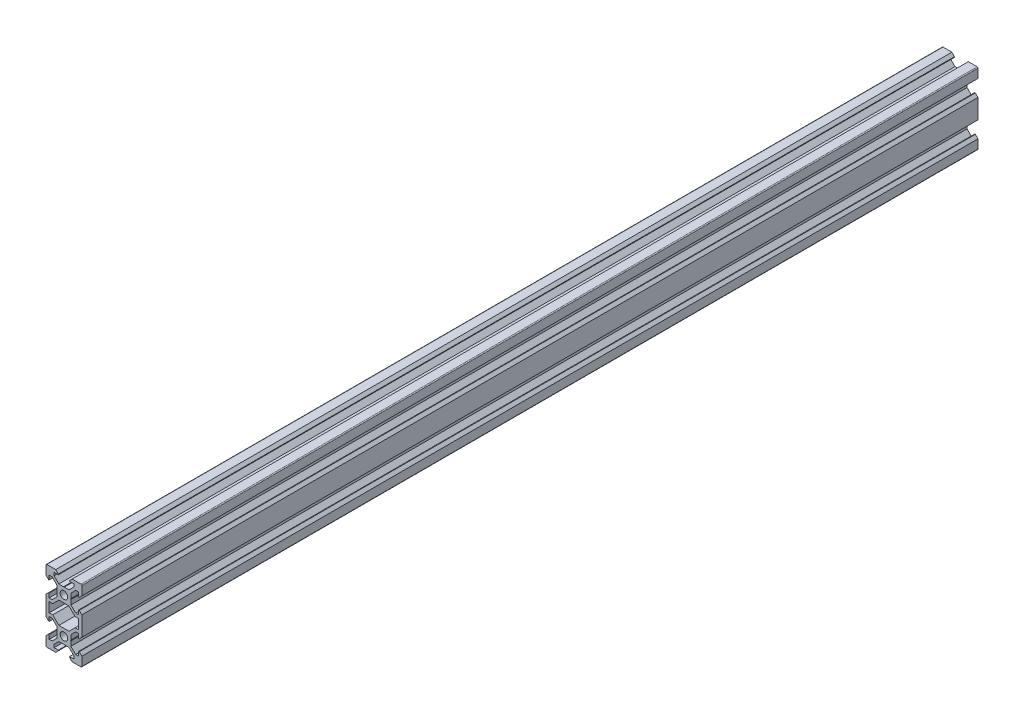
SolidWorks part; units mm, degrees
material "6061-T6 (SS)"
ref_plane "Front Plane" through (0, 0, 0) normal (0, 0, 1) x (1, 0, 0)
ref_plane "Top Plane" through (0, 0, 0) normal (0, 1, 0) x (1, 0, 0)
ref_plane "Right Plane" through (0, 0, 0) normal (1, 0, 0) x (0, 0, -1)
sketch "Sketch1" plane through (0, 0, 0) normal (0, 0, 1) x (1, 0, 0)
  line L0 (0, 0) -> (10, 0) construction
  line L1 (9.5, -20) -> (-9.5, -20)
  line L2 (10, -19.5) -> (10, 19.5)
  line L3 (9.5, 20) -> (-9.5, 20)
  line L4 (-10, -19.5) -> (-10, 19.5)
  line L5 (10, -20) -> (-10, 20) construction
  line L6 (10, 20) -> (-10, -20) construction
  circle A0 centre (0, 10) radius 2.1
  circle A1 centre (0, -10) radius 2.1
  arc A2 (-9.5, -20) -> (-10, -19.5) centre (-9.5, -19.5) cw
  arc A3 (9.5, -20) -> (10, -19.5) centre (9.5, -19.5) ccw
  arc A4 (10, 19.5) -> (9.5, 20) centre (9.5, 19.5) ccw
  arc A5 (-9.5, 20) -> (-10, 19.5) centre (-9.5, 19.5) ccw
  point P0 (0, 0)
  line B0 (0, 10) -> (0, 20) construction
  line B1 (0, 13.69) -> (-0.21, 13.9)
  line B2 (-0.21, 13.9) -> (-2.8393, 13.9)
  line B3 (-2.8393, 13.9) -> (-5.5, 16.5607)
  line B4 (-5.5, 16.5607) -> (-5.5, 18.2)
  line B5 (-5.5, 18.2) -> (-3.125, 18.2)
  line B6 (-3.125, 18.2) -> (-3.125, 18.545)
  line B7 (-3.125, 18.545) -> (-4.58, 20)
  line B8 (-4.58, 20) -> (4.58, 20)
  line B9 (0, 10) -> (-5.9132, 15.9132) construction
  line B10 (3.125, 18.545) -> (4.58, 20)
  line B11 (3.125, 18.2) -> (3.125, 18.545)
  line B12 (5.5, 18.2) -> (3.125, 18.2)
  line B13 (5.5, 16.5607) -> (5.5, 18.2)
  line B14 (2.8393, 13.9) -> (5.5, 16.5607)
  line B15 (0.21, 13.9) -> (2.8393, 13.9)
  line B16 (0, 13.69) -> (0.21, 13.9)
  line B17 (0, 10) -> (-10, 10) construction
  line B18 (-3.69, 10) -> (-3.9, 9.79)
  line B19 (-3.9, 9.79) -> (-3.9, 7.1607)
  line B20 (-3.9, 7.1607) -> (-6.5607, 4.5)
  line B21 (-6.5607, 4.5) -> (-8.2, 4.5)
  line B22 (-8.2, 4.5) -> (-8.2, 6.875)
  line B23 (-8.2, 6.875) -> (-8.545, 6.875)
  line B24 (-8.545, 6.875) -> (-10, 5.42)
  line B25 (-10, 5.42) -> (-10, 14.58)
  line B26 (0, 10) -> (-5.9132, 4.0868) construction
  line B27 (-8.545, 13.125) -> (-10, 14.58)
  line B28 (-8.2, 13.125) -> (-8.545, 13.125)
  line B29 (-8.2, 15.5) -> (-8.2, 13.125)
  line B30 (-6.5607, 15.5) -> (-8.2, 15.5)
  line B31 (-3.9, 12.8393) -> (-6.5607, 15.5)
  line B32 (-3.9, 10.21) -> (-3.9, 12.8393)
  line B33 (-3.69, 10) -> (-3.9, 10.21)
  line B34 (0, -10) -> (-10, -10) construction
  line B35 (-3.69, -10) -> (-3.9, -10.21)
  line B36 (-3.9, -10.21) -> (-3.9, -12.8393)
  line B37 (-3.9, -12.8393) -> (-6.5607, -15.5)
  line B38 (-6.5607, -15.5) -> (-8.2, -15.5)
  line B39 (-8.2, -15.5) -> (-8.2, -13.125)
  line B40 (-8.2, -13.125) -> (-8.545, -13.125)
  line B41 (-8.545, -13.125) -> (-10, -14.58)
  line B42 (-10, -14.58) -> (-10, -5.42)
  line B43 (0, -10) -> (-5.9132, -15.9132) construction
  line B44 (-8.545, -6.875) -> (-10, -5.42)
  line B45 (-8.2, -6.875) -> (-8.545, -6.875)
  line B46 (-8.2, -4.5) -> (-8.2, -6.875)
  line B47 (-6.5607, -4.5) -> (-8.2, -4.5)
  line B48 (-3.9, -7.1607) -> (-6.5607, -4.5)
  line B49 (-3.9, -9.79) -> (-3.9, -7.1607)
  line B50 (-3.69, -10) -> (-3.9, -9.79)
  line B51 (0, -10) -> (0, -20) construction
  line B52 (0, -13.69) -> (0.21, -13.9)
  line B53 (0.21, -13.9) -> (2.8393, -13.9)
  line B54 (2.8393, -13.9) -> (5.5, -16.5607)
  line B55 (5.5, -16.5607) -> (5.5, -18.2)
  line B56 (5.5, -18.2) -> (3.125, -18.2)
  line B57 (3.125, -18.2) -> (3.125, -18.545)
  line B58 (3.125, -18.545) -> (4.58, -20)
  line B59 (4.58, -20) -> (-4.58, -20)
  line B60 (0, -10) -> (5.9132, -15.9132) construction
  line B61 (-3.125, -18.545) -> (-4.58, -20)
  line B62 (-3.125, -18.2) -> (-3.125, -18.545)
  line B63 (-5.5, -18.2) -> (-3.125, -18.2)
  line B64 (-5.5, -16.5607) -> (-5.5, -18.2)
  line B65 (-2.8393, -13.9) -> (-5.5, -16.5607)
  line B66 (-0.21, -13.9) -> (-2.8393, -13.9)
  line B67 (0, -13.69) -> (-0.21, -13.9)
  line B68 (0, -10) -> (10, -10) construction
  line B69 (3.69, -10) -> (3.9, -9.79)
  line B70 (3.9, -9.79) -> (3.9, -7.1607)
  line B71 (3.9, -7.1607) -> (6.5607, -4.5)
  line B72 (6.5607, -4.5) -> (8.2, -4.5)
  line B73 (8.2, -4.5) -> (8.2, -6.875)
  line B74 (8.2, -6.875) -> (8.545, -6.875)
  line B75 (8.545, -6.875) -> (10, -5.42)
  line B76 (10, -5.42) -> (10, -14.58)
  line B77 (0, -10) -> (5.9132, -4.0868) construction
  line B78 (8.545, -13.125) -> (10, -14.58)
  line B79 (8.2, -13.125) -> (8.545, -13.125)
  line B80 (8.2, -15.5) -> (8.2, -13.125)
  line B81 (6.5607, -15.5) -> (8.2, -15.5)
  line B82 (3.9, -12.8393) -> (6.5607, -15.5)
  line B83 (3.9, -10.21) -> (3.9, -12.8393)
  line B84 (3.69, -10) -> (3.9, -10.21)
  line B85 (0, 10) -> (10, 10) construction
  line B86 (3.69, 10) -> (3.9, 10.21)
  line B87 (3.9, 10.21) -> (3.9, 12.8393)
  line B88 (3.9, 12.8393) -> (6.5607, 15.5)
  line B89 (6.5607, 15.5) -> (8.2, 15.5)
  line B90 (8.2, 15.5) -> (8.2, 13.125)
  line B91 (8.2, 13.125) -> (8.545, 13.125)
  line B92 (8.545, 13.125) -> (10, 14.58)
  line B93 (10, 14.58) -> (10, 5.42)
  line B94 (0, 10) -> (5.9132, 15.9132) construction
  line B95 (8.545, 6.875) -> (10, 5.42)
  line B96 (8.2, 6.875) -> (8.545, 6.875)
  line B97 (8.2, 4.5) -> (8.2, 6.875)
  line B98 (6.5607, 4.5) -> (8.2, 4.5)
  line B99 (3.9, 7.1607) -> (6.5607, 4.5)
  line B100 (3.9, 9.79) -> (3.9, 7.1607)
  line B101 (3.69, 10) -> (3.9, 9.79)
  line B102 (-8.2, -2.7) -> (-8.2, 2.7)
  line B103 (-8.2, 2.7) -> (-6.2393, 2.7)
  line B104 (-6.2393, 2.7) -> (-2.8393, 6.1)
  line B105 (-2.8393, 6.1) -> (2.8393, 6.1)
  line B106 (0, 6.1) -> (0, 0) construction
  line B107 (0, 0) -> (-8.2, 0) construction
  line B108 (6.2393, 2.7) -> (2.8393, 6.1)
  line B109 (8.2, 2.7) -> (6.2393, 2.7)
  line B110 (8.2, -2.7) -> (8.2, 2.7)
  line B111 (8.2, -2.7) -> (6.2393, -2.7)
  line B112 (6.2393, -2.7) -> (2.8393, -6.1)
  line B113 (-2.8393, -6.1) -> (2.8393, -6.1)
  line B114 (-6.2393, -2.7) -> (-2.8393, -6.1)
  line B115 (-8.2, -2.7) -> (-6.2393, -2.7)
  line B116 (0, 6.1) -> (0, 10) construction
  line B117 (0, 10) -> (-5.0927, 4.9073) construction
  dimension "D4" = 4.2
  dimension "D5" = 0.5
  dimension "D1" = 20
  dimension "D2" = 40
  dimension "D3" = 20
sketch_block_instance "V Slot 1-4"
sketch_block "V Slot 1" parameters "D1"=10, "D2"=11, "D3"=4.3, "D4"=1.8, "D5"=0.21, "D6"=45, "D7"=9.16, "D8"=1.5, "D9"=6.25
sketch_block_instance "V Slot 1-5"
sketch_block_instance "V Slot 1-6"
sketch_block_instance "V Slot 1-7"
sketch_block_instance "V Slot 1-8"
sketch_block_instance "V Slot 1-9"
sketch_block_instance "Center Cutout 1-1"
sketch_block "Center Cutout 1" parameters "D1"=5.4, "D2"=12.2, "D3"=8.2, "D4"=45, "D5"=10, "D6"=1.5
extrude "Boss-Extrude1" add sketch "Sketch1" along normal blind 500 contours B101 B86 B87 B88 B89 B90 B91 B92 L2 A4 L3 B10 B11 B12 B13 B14 B15 B16 B1 B2 B3 B4 B5 B6 B7 A5 L4 B27 B28 B29 B30 B31 B32 B33 B18 B19 B20 B21 B22 B23 B24 B44 B45 B46 B47 B48 B49 B50 B35
equation "\"L\"= 500"
equation "\"D1@Boss-Extrude1\"=\"L\""
